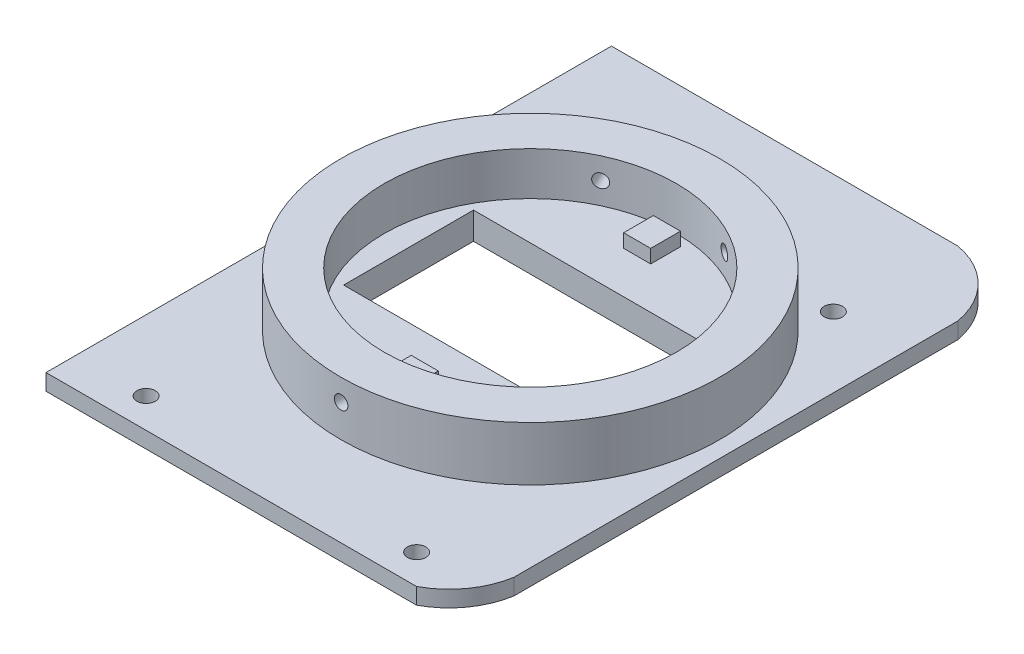
SolidWorks part; units mm, degrees
ref_plane "Front Plane" through (0, 0, 0) normal (0, 0, 1) x (1, 0, 0)
ref_plane "Top Plane" through (0, 0, 0) normal (0, 1, 0) x (1, 0, 0)
ref_plane "Right Plane" through (0, 0, 0) normal (1, 0, 0) x (0, 0, -1)
sketch "Sketch1" plane through (0, 0, 0) normal (0, 1, 0) x (1, 0, 0)
  line L1 (-30, 51) -> (30, 51)
  line L2 (-30, 51) -> (-30, -51)
  line L3 (-30, -51) -> (30, -51)
  line L4 (30, 51) -> (30, -51)
  line L5 (-30, 51) -> (30, -51) construction
  line L6 (-30, -51) -> (30, 51) construction
  point P0 (0, 0)
  dimension "D1" = 60
  dimension "D2" = 102
extrude "Boss-Extrude1" add sketch "Sketch1" along normal blind 3
hole_wizard "M3 Clearance Hole1" positions "3DSketch1" profile "Sketch3" hole size "M3" standard "ANSI Metric" end condition through all
sketch3d "3DSketch1"
  line L0 (-30, 3, -51) -> (-30, 3, 51) construction
  line L1 (30, 3, -51) -> (-30, 3, -51) construction
  line L2 (30, 3, 51) -> (30, 3, -51) construction
  point P0 (-25, 3, -36)
  point P2 (25, 3, -36)
  point P4 (-25, 3, 41)
  point P6 (25, 3, 41)
  dimension "D1" = 5
  dimension "D2" = 15
  dimension "D3" = 15
  dimension "D4" = 50
  dimension "D5" = 5
  dimension "D6" = 77
  dimension "D7" = 5
  dimension "D8" = 77
sketch "Sketch3" plane through (-25, 3, -36) normal (1, 0, 0) x (0, 0, 1)
  line L0 (0, 0) -> (0, 3)
  line L1 (0, 3) -> (1.7, 3)
  line L2 (1.7, 3) -> (1.7, 0)
  line L5 (1.7, 0) -> (0, 0)
  line L11 (0, -6.35) -> (0, 107.95) construction
  dimension "Thru Hole Dia." = 3.4
  dimension "Thru Hole Depth" = 3
sketch "Sketch5" plane through (0, 3, 0) normal (0, 1, 0) x (1, 0, 0)
  line L0 (30, 51) -> (-30, 51) construction
  line L1 (-30, 51) -> (-30, -51) construction
  circle A0 centre (0, 5) radius 35
  dimension "D3" = 70
  dimension "D1" = 46
  dimension "D2" = 30
extrude "Boss-Extrude2" add sketch "Sketch5" along normal blind 10
sketch "Sketch6" plane through (0, 13, 0) normal (0, 1, 0) x (1, 0, 0)
  line L0 (30, 51) -> (-30, 51) construction
  line L1 (-30, 51) -> (-30, 23.0278) construction
  circle A0 centre (0, 5) radius 27
  dimension "D3" = 54
  dimension "D1" = 46
  dimension "D2" = 30
extrude "Cut-Extrude1" cut sketch "Sketch6" against normal blind 8
sketch "Sketch8" plane through (0, 5, 0) normal (0, 1, 0) x (1, 0, 0)
  line L1 (-2.5, 30.25) -> (2.5, 30.25)
  line L2 (-2.5, 30.25) -> (-2.5, 24.75)
  line L3 (-2.5, 24.75) -> (2.5, 24.75)
  line L4 (2.5, 30.25) -> (2.5, 24.75)
  line L5 (-2.5, 30.25) -> (2.5, 24.75) construction
  line L6 (-2.5, 24.75) -> (2.5, 30.25) construction
  point P0 (0, 27.5)
  dimension "D1" = 5.5
  dimension "D2" = 5
  dimension "D3" = 0
  dimension "D4" = 27.5
extrude "Boss-Extrude3" add sketch "Sketch8" along normal blind 2.5
sketch "Sketch9" plane through (0, 5, 0) normal (0, 1, 0) x (1, 0, 0)
  line L1 (-2.5, -14.5) -> (2.5, -14.5)
  line L2 (-2.5, -14.5) -> (-2.5, -19.5)
  line L3 (-2.5, -19.5) -> (2.5, -19.5)
  line L4 (2.5, -14.5) -> (2.5, -19.5)
  line L5 (-2.5, -14.5) -> (2.5, -19.5) construction
  line L6 (-2.5, -19.5) -> (2.5, -14.5) construction
  point P0 (0, -17)
  dimension "D1" = 5
  dimension "D2" = 5
  dimension "D3" = 0
  dimension "D4" = 17
extrude "Boss-Extrude4" add sketch "Sketch9" along normal blind 2.5
sketch "Sketch10" plane through (0, 5, 0) normal (0, 1, 0) x (1, 0, 0)
  line L1 (-22.5, 17) -> (22.5, 17)
  line L2 (-22.5, 17) -> (-22.5, -7)
  line L3 (-22.5, -7) -> (22.5, -7)
  line L4 (22.5, 17) -> (22.5, -7)
  line L5 (-22.5, 17) -> (22.5, -7) construction
  line L6 (-22.5, -7) -> (22.5, 17) construction
  point P0 (0, 5)
  dimension "D1" = 5
  dimension "D2" = 45
  dimension "D3" = 24
extrude "Cut-Extrude2" cut sketch "Sketch10" against normal through all
sketch "Sketch12" plane through (0, 3, 0) normal (0, 1, 0) x (1, 0, 0)
  line L0 (-30, 51) -> (-30, 23.0278) construction
  line L1 (30, 51) -> (-30, 51)
  line L2 (30, 51) -> (30, 49)
  line L3 (30, 49) -> (-30, 49)
  line L4 (-30, 51) -> (-30, 49)
  dimension "D1" = 2
extrude "Cut-Extrude3" cut sketch "Sketch12" against normal through all
sketch "Sketch13" plane through (0, 3, 0) normal (0, 1, 0) x (1, 0, 0)
  line L0 (-30, 49) -> (-30, 23.0278) construction
  line L1 (30, -51) -> (-30, -51)
  line L2 (30, -51) -> (30, -48)
  line L3 (30, -48) -> (-30, -48)
  line L4 (-30, -51) -> (-30, -48)
  dimension "D1" = 3
extrude "Cut-Extrude4" cut sketch "Sketch13" against normal through all
sketch "Sketch14" plane through (0, 0, -49) normal (0, 0, -1) x (-1, 0, 0)
  line L1 (30, 3) -> (-30, 3)
  line L2 (30, 3) -> (30, 0)
  line L3 (30, 0) -> (-30, 0)
  line L4 (-30, 3) -> (-30, 0)
extrude "Boss-Extrude5" add sketch "Sketch14" along normal blind 9
sketch "Sketch16" plane through (-30, 0, 0) normal (-1, 0, 0) x (0, 0, 1)
  line L1 (-58, 0) -> (48, 0)
  line L2 (-58, 0) -> (-58, 3)
  line L3 (-58, 3) -> (48, 3)
  line L4 (48, 0) -> (48, 3)
extrude "Boss-Extrude6" add sketch "Sketch16" along normal blind 8
sketch "Sketch17" plane through (30, 0, 0) normal (1, 0, 0) x (0, 0, -1)
  line L1 (58, 3) -> (-48, 3)
  line L2 (58, 3) -> (58, 0)
  line L3 (58, 0) -> (-48, 0)
  line L4 (-48, 3) -> (-48, 0)
extrude "Boss-Extrude7" add sketch "Sketch17" along normal blind 8
sketch "Sketch18" plane through (0, 3, 0) normal (0, 1, 0) x (1, 0, 0)
  line L0 (38, 58) -> (38, -48) construction
  line L1 (-38, 58) -> (38, 58) construction
  line L2 (38, 46) -> (38, 58)
  line L3 (38, 58) -> (26, 58)
  arc A0 (38, 46) -> (26, 58) centre (23.389, 43.389) ccw
  dimension "D1" = 12
  dimension "D2" = 12
extrude "Cut-Extrude5" cut sketch "Sketch18" against normal blind 15
sketch "Sketch19" plane through (0, 3, 0) normal (0, 1, 0) x (1, 0, 0)
  line L0 (38, 46) -> (38, -48) construction
  line L1 (38, -48) -> (-38, -48) construction
  line L2 (38, -36) -> (38, -48)
  line L3 (38, -48) -> (26, -48)
  arc A0 (38, -36) -> (26, -48) centre (23.6646, -33.6646) cw
  dimension "D1" = 12
  dimension "D2" = 12
extrude "Cut-Extrude6" cut sketch "Sketch19" against normal through all
sketch "Sketch20" plane through (0, 3, 0) normal (0, 1, 0) x (1, 0, 0)
  line L0 (0, 58) -> (0, -48)
  line L1 (-38, 58) -> (26, 58) construction
  line L2 (26, -48) -> (-38, -48) construction
hole_wizard "M3x0.5 Tapped Hole1" positions "3DSketch2" profile "Sketch22" tap size "M3x0.5" standard "ANSI Metric"
sketch3d "3DSketch2"
  line L0 (0, 3, -58) -> (0, 3, 48) construction
  point P0 (-14.8324, 9, -36.7017)
  dimension "D1" = 6
  dimension "D2" = 16
sketch "Sketch22" plane through (-14.8324, 9, -36.7017) normal (0, 1, 0) x (-0.9058, 0, 0.4238)
  line L0 (0, 0) -> (0, 8)
  line L1 (0, 8) -> (1.25, 8)
  line L2 (1.25, 8) -> (1.25, 0)
  line L5 (1.25, 0) -> (0, 0)
  line L11 (0, -6.35) -> (0, 107.95) construction
  dimension "Thread Major Dia." = 2.5
  dimension "Thru Tap Drill Depth" = 8
hole_wizard "M3x0.5 Tapped Hole2" positions "3DSketch3" profile "Sketch23" tap size "M3x0.5" standard "ANSI Metric"
sketch3d "3DSketch3"
  line L0 (0, 3, -58) -> (0, 3, 48) construction
  point P0 (14.8324, 9, -36.7017)
  dimension "D1" = 6
  dimension "D2" = 16
sketch "Sketch23" plane through (14.8324, 9, -36.7017) normal (0, 1, 0) x (-0.9058, 0, -0.4238)
  line L0 (0, 0) -> (0, 8)
  line L1 (0, 8) -> (1.25, 8)
  line L2 (1.25, 8) -> (1.25, 0)
  line L5 (1.25, 0) -> (0, 0)
  line L11 (0, -6.35) -> (0, 107.95) construction
  dimension "Thread Major Dia." = 2.5
  dimension "Thru Tap Drill Depth" = 8
hole_wizard "M3x0.5 Tapped Hole3" positions "3DSketch7" profile "Sketch27" tap size "M3x0.5" standard "ANSI Metric"
sketch3d "3DSketch7"
  point P0 (0.02, 9, 30)
  dimension "D1" = 6
  dimension "D2" = 38.02
sketch "Sketch27" plane through (0.02, 9, 30) normal (0, 1, 0) x (1, 0, -0.0006)
  line L0 (0, 0) -> (0, 8)
  line L1 (0, 8) -> (1.25, 8)
  line L2 (1.25, 8) -> (1.25, 0)
  line L5 (1.25, 0) -> (0, 0)
  line L11 (0, -6.35) -> (0, 107.95) construction
  dimension "Thread Major Dia." = 2.5
  dimension "Thru Tap Drill Depth" = 8
sketch "Sketch28" plane through (0, 3, 0) normal (0, 1, 0) x (1, 0, 0)
  line L1 (-38, -48) -> (38, -48)
  line L2 (-38, -48) -> (-38, -46.5)
  line L3 (-38, -46.5) -> (38, -46.5)
  line L4 (38, -48) -> (38, -46.5)
  dimension "D1" = 1.5
extrude "Cut-Extrude7" cut sketch "Sketch28" against normal through all
sketch "Sketch29" plane through (0, 0, 0) normal (0, -1, 0) x (1, 0, 0)
  line L0 (0, 46.414) -> (0, -51.2556)
  line L1 (0, -58) -> (0, 48) construction
  line L2 (-32.3165, -5) -> (32.6058, -5)
